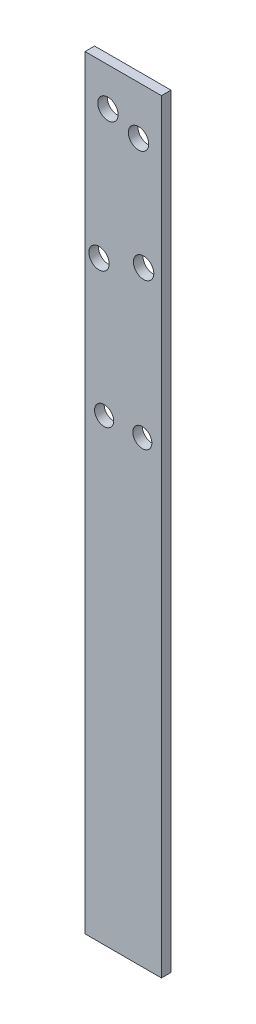
SolidWorks part; units mm, degrees
ref_plane "Front Plane" through (0, 0, 0) normal (0, 0, 1) x (1, 0, 0)
ref_plane "Top Plane" through (0, 0, 0) normal (0, 1, 0) x (1, 0, 0)
ref_plane "Right Plane" through (0, 0, 0) normal (1, 0, 0) x (0, 0, -1)
sketch "Sketch2" plane through (0, 0, 0) normal (0, 0, 1) x (1, 0, 0)
  line L1 (0, 0) -> (38.1, 0)
  line L2 (0, 0) -> (0, -381)
  line L3 (0, -381) -> (38.1, -381)
  line L4 (38.1, 0) -> (38.1, -381)
  line L8 (0, -126.2724) -> (38.1, -126.2724) construction
  line L9 (19.05, -132.3412) -> (0, -132.3412) construction
  line L10 (19.05, -136.9725) -> (38.1, -136.9725) construction
  line L16 (11.43, -19.05) -> (26.67, -19.05) construction
  line L17 (6.985, -85.725) -> (29.21, -85.725) construction
  circle A6 centre (11.43, -19.05) radius 5.08
  circle A7 centre (26.67, -24.13) radius 5.08
  circle A8 centre (6.985, -85.725) radius 5.08
  circle A9 centre (29.21, -78.74) radius 5.08
  circle A10 centre (9.525, -152.4) radius 4.7625
  circle A11 centre (28.575, -152.4) radius 4.7625
  point P13 (9.525, -132.3412)
  point P16 (28.575, -136.9725)
  point P17 (29.21, -146.2351)
  point P18 (19.05, -136.9725)
  point P19 (19.05, -126.2724)
  point P20 (29.21, -115.5228)
  point P41 (19.05, -19.05)
  point P43 (19.05, 0)
  dimension "D19" = 10.16
  dimension "D20" = 19.05
  dimension "D4" = 9.525
  dimension "D1" = 38.1
  dimension "D2" = 381
  dimension "D3" = 8.89
  dimension "D5" = 152.4
  dimension "D21" = 24.13
  dimension "D22" = 85.725
  dimension "D23" = 78.74
  dimension "D24" = 15.24
  dimension "D25" = 22.225
extrude "Boss-Extrude2" add sketch "Sketch2" along normal blind 4.7625
